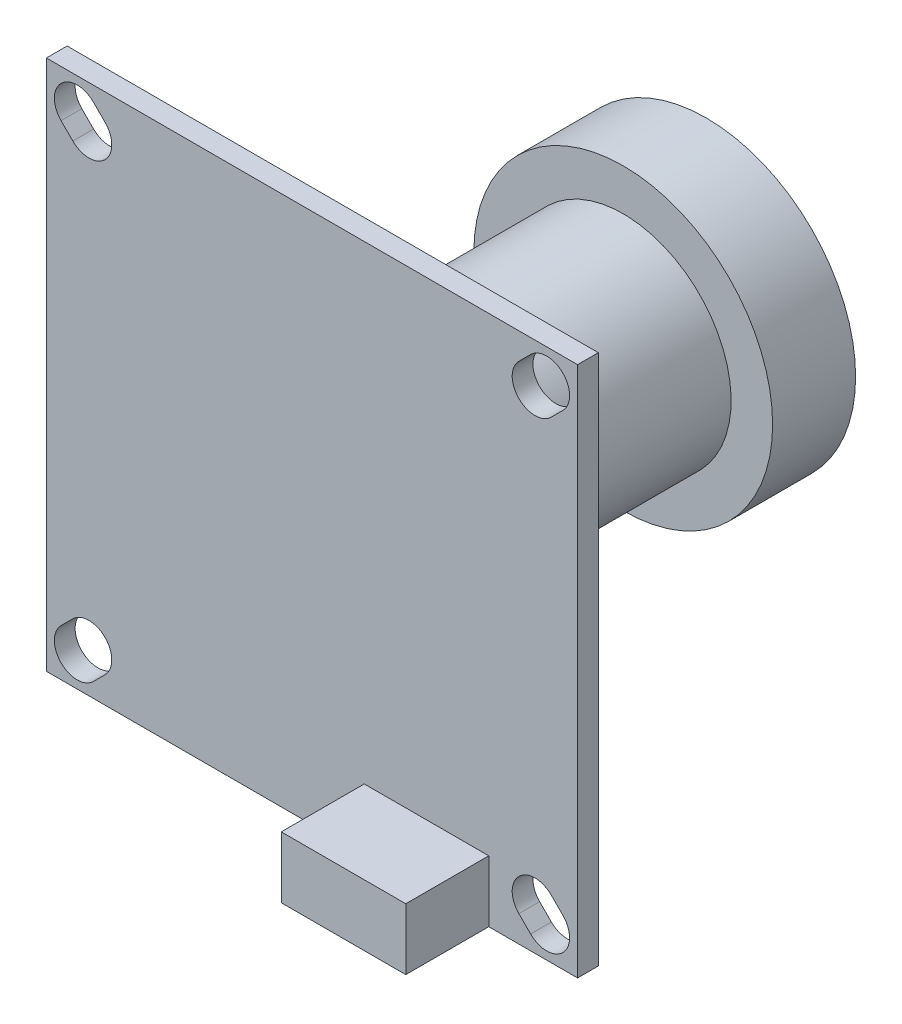
SolidWorks part; units mm, degrees
ref_plane "Plan de face" through (0, 0, 0) normal (0, 0, 1) x (1, 0, 0)
ref_plane "Plan de dessus" through (0, 0, 0) normal (0, 1, 0) x (1, 0, 0)
ref_plane "Plan de droite" through (0, 0, 0) normal (1, 0, 0) x (0, 0, -1)
sketch "Esquisse1" plane through (0, 0, 0) normal (0, 0, 1) x (1, 0, 0)
  line L0 (-14.1438, 14.1438) -> (-13.4367, 13.4367) construction
  line L1 (-16, 16) -> (16, 16)
  line L2 (-16, 16) -> (-16, -16)
  line L3 (-16, -16) -> (16, -16)
  line L4 (16, 16) -> (16, -16)
  line L5 (-13.1716, 15.1161) -> (-12.4645, 14.409)
  line L6 (-15.1161, 13.1716) -> (-14.409, 12.4645)
  line L7 (-16, 16) -> (16, -16) construction
  line L8 (14.1438, 14.1438) -> (13.4367, 13.4367) construction
  line L9 (15.1161, 13.1716) -> (14.409, 12.4645)
  line L10 (13.1716, 15.1161) -> (12.4645, 14.409)
  line L11 (14.1438, -14.1438) -> (13.4367, -13.4367) construction
  line L12 (13.1716, -15.1161) -> (12.4645, -14.409)
  line L13 (15.1161, -13.1716) -> (14.409, -12.4645)
  line L14 (-14.1438, -14.1438) -> (-13.4367, -13.4367) construction
  line L15 (-15.1161, -13.1716) -> (-14.409, -12.4645)
  line L16 (-13.1716, -15.1161) -> (-12.4645, -14.409)
  arc A0 (-13.1716, 15.1161) -> (-15.1161, 13.1716) centre (-14.1438, 14.1438) ccw
  arc A1 (-14.409, 12.4645) -> (-12.4645, 14.409) centre (-13.4367, 13.4367) ccw
  arc A2 (15.1161, 13.1716) -> (13.1716, 15.1161) centre (14.1438, 14.1438) ccw
  arc A3 (12.4645, 14.409) -> (14.409, 12.4645) centre (13.4367, 13.4367) ccw
  arc A4 (13.1716, -15.1161) -> (15.1161, -13.1716) centre (14.1438, -14.1438) ccw
  arc A5 (14.409, -12.4645) -> (12.4645, -14.409) centre (13.4367, -13.4367) ccw
  arc A6 (-15.1161, -13.1716) -> (-13.1716, -15.1161) centre (-14.1438, -14.1438) ccw
  arc A7 (-12.4645, -14.409) -> (-14.409, -12.4645) centre (-13.4367, -13.4367) ccw
  point P4 (-13.7903, 13.7903)
  point P7 (-13.7903, 13.7903)
  point P12 (0, 0)
  point P13 (0, 0)
  point P19 (13.7903, 13.7903)
  point P26 (13.7903, -13.7903)
  point P33 (-13.7903, -13.7903)
  point P38 (0, 0)
  dimension "D3" = 1
  dimension "D1" = 32
  dimension "D2" = 2.75
  dimension "D4" = 2.625
  dimension "D6" = 2.2097
  dimension "D5" = 4
extrude "Boss.-Extru.1" add sketch "Esquisse1" along normal blind 1.25
sketch "Esquisse2" plane through (0, 0, 1.25) normal (0, 0, 1) x (1, 0, 0)
  line L0 (-16, -16) -> (16, -16) construction
  line L1 (10.65, -16) -> (3.15, -16)
  line L2 (10.65, -16) -> (10.65, -12.3)
  line L3 (10.65, -12.3) -> (3.15, -12.3)
  line L4 (3.15, -16) -> (3.15, -12.3)
  line L5 (16, -16) -> (16, 16) construction
  dimension "D1" = 5.35
  dimension "D2" = 7.5
  dimension "D3" = 3.7
extrude "Boss.-Extru.2" add sketch "Esquisse2" along normal blind 5
sketch "Esquisse3" plane through (0, 0, 0) normal (0, 0, -1) x (-1, 0, 0)
  line L0 (-6.5, 6.5) -> (6.5, 6.5)
  line L1 (6.5, 6.5) -> (6.5, 2)
  line L2 (6.5, 2) -> (8.5, 2)
  line L3 (8.5, -2) -> (6.5, -2)
  line L4 (6.5, -2) -> (6.5, -6.5)
  line L5 (6.5, -6.5) -> (-6.5, -6.5)
  line L6 (-6.5, -6.5) -> (-6.5, -2)
  line L7 (-6.5, -2) -> (-8.5, -2)
  line L8 (-8.5, 2) -> (-6.5, 2)
  line L9 (-6.5, 2) -> (-6.5, 6.5)
  line L10 (-6.5, 6.5) -> (6.5, -6.5) construction
  line L11 (-16, 16) -> (16, 16) construction
  line L12 (16, 16) -> (16, -16) construction
  arc A0 (8.5, 2) -> (8.5, -2) centre (8.5, 0) cw
  arc A1 (-8.5, -2) -> (-8.5, 2) centre (-8.5, 0) cw
  point P13 (0, 0)
  point P17 (0, 16)
  point P22 (16, 0)
  dimension "D3" = 2
  dimension "D1" = 13
  dimension "D2" = 13
  dimension "D4" = 2
extrude "Boss.-Extru.3" add sketch "Esquisse3" along normal blind 3.5
sketch "Esquisse4" plane through (0, 0, -3.5) normal (0, 0, -1) x (-1, 0, 0)
  line L0 (6.5, 6.5) -> (-6.5, 6.5) construction
  circle A0 centre (0, 0) radius 6.5
extrude "Boss.-Extru.4" add sketch "Esquisse4" along normal blind 14
sketch "Esquisse5" plane through (0, 0, -17.5) normal (0, 0, -1) x (-1, 0, 0)
  circle A0 centre (0, 0) radius 9
  dimension "D1" = 18
extrude "Boss.-Extru.5" add sketch "Esquisse5" along normal blind 5
sketch "Esquisse6" plane through (0, 0, 0) normal (1, 0, 0) x (0, 0, -1)
  line L0 (22.5, 0) -> (24.5, 0)
  line L1 (22.5, -9) -> (22.5, 9) construction
  line L2 (22.5, -9) -> (22.5, 9) construction
  line L3 (24.5, 0) -> (24.5, -1.7553) construction
  line L4 (22.5, 0) -> (22.5, 9)
  arc A0 (24.5, 0) -> (22.5, 9) centre (3.25, 0) ccw
  point P5 (22.5, 0)
  dimension "D1" = 2
revolve "Révolution2" add sketch "Esquisse6" angle 360 about L0
